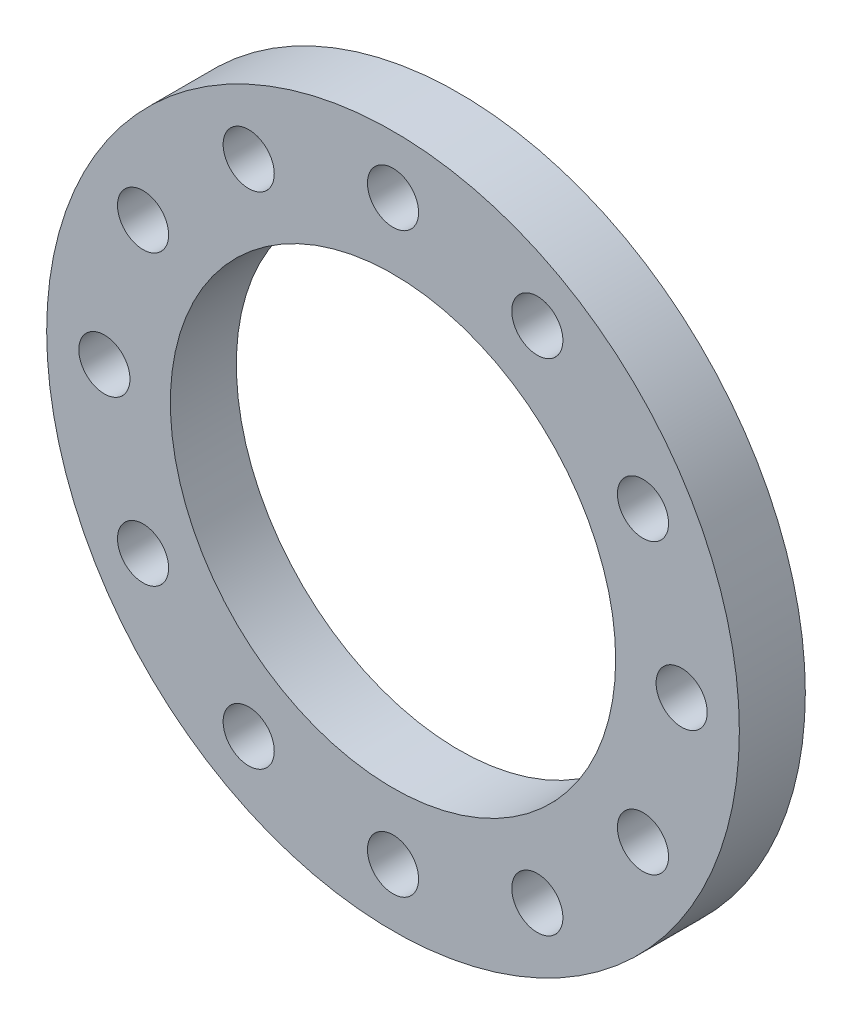
SolidWorks part; units mm, degrees
material "Thornel Mat VMA"
ref_plane "前视基准面" through (0, 0, 0) normal (0, 0, 1) x (1, 0, 0)
ref_plane "上视基准面" through (0, 0, 0) normal (0, 1, 0) x (1, 0, 0)
ref_plane "右视基准面" through (0, 0, 0) normal (1, 0, 0) x (0, 0, -1)
sketch "草图1" plane through (0, 0, 0) normal (0, 0, 1) x (1, 0, 0)
  line L0 (0, 0) -> (17.5, 0) construction
  circle A0 centre (0, 0) radius 21
  circle A1 centre (0, 0) radius 13.5
  circle A2 centre (0, 0) radius 17.5 construction
  circle A3 centre (0, 17.5) radius 1.55
  circle A4 centre (17.5, 0) radius 1.55
  circle A5 centre (0, -17.5) radius 1.55
  circle A6 centre (-17.5, 0) radius 1.55
  circle A7 centre (15.1554, -8.75) radius 1.55
  circle A8 centre (8.75, 15.1554) radius 1.55
  circle A9 centre (-15.1554, 8.75) radius 1.55
  circle A10 centre (-8.75, -15.1554) radius 1.55
  circle A11 centre (-15.1554, -8.75) radius 1.55
  circle A12 centre (8.75, -15.1554) radius 1.55
  circle A13 centre (15.1554, 8.75) radius 1.55
  circle A14 centre (-8.75, 15.1554) radius 1.55
  dimension "D1" = 42
  dimension "D2" = 27
  dimension "D3" = 35
  dimension "D4" = 3.1
  dimension "D6" = 17.5
  dimension "D5" = 3
extrude "凸台-拉伸1" add sketch "草图1" along normal blind 4
